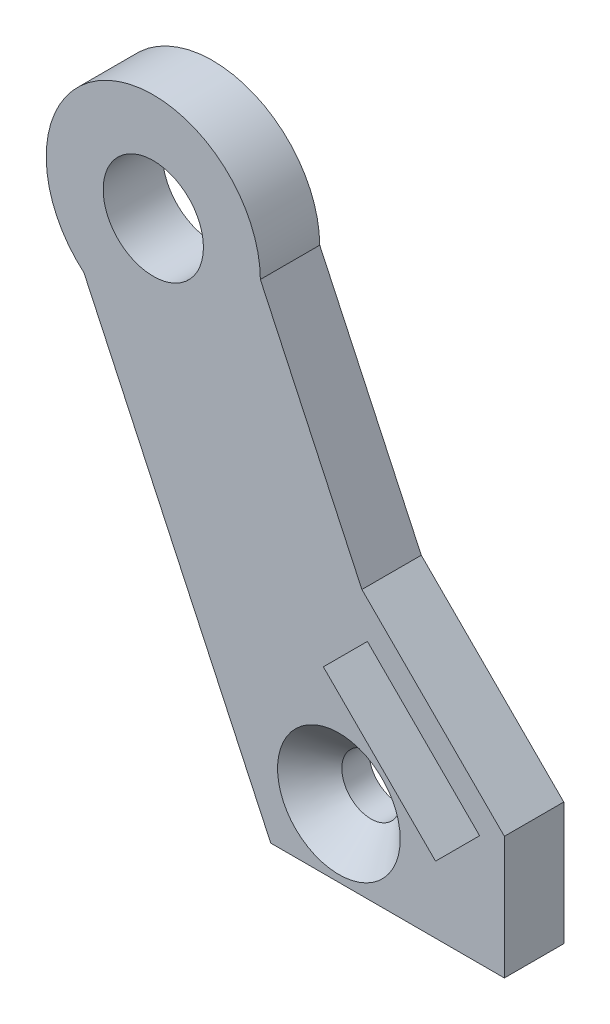
SolidWorks part; units mm, degrees
ref_plane "Front Plane" through (0, 0, 0) normal (0, 0, 1) x (1, 0, 0)
ref_plane "Top Plane" through (0, 0, 0) normal (0, 1, 0) x (1, 0, 0)
ref_plane "Right Plane" through (0, 0, 0) normal (1, 0, 0) x (0, 0, -1)
sketch "Sketch1" plane through (0, 0, 0) normal (0, 0, 1) x (1, 0, 0)
  line L0 (0, 12) -> (12, 0) construction
  line L1 (0, 0) -> (12, 0)
  line L2 (0, 0) -> (0, 12)
  line L3 (0, 12) -> (12, 12)
  line L4 (12, 0) -> (12, 12)
  line L5 (0, 0) -> (3.5, 0)
  line L6 (0, 0) -> (0, 3.5)
  line L7 (0, 3.5) -> (3.5, 3.5)
  line L8 (3.5, 0) -> (3.5, 3.5)
  line L9 (8.2662, 3.6278) -> (8.3192, 3.6808) construction
  line L10 (8.4645, 3.4295) -> (2.7015, 9.1924)
  line L11 (2.7015, 9.1924) -> (4.9643, 11.4551)
  line L12 (8.4645, 3.4295) -> (10.7272, 5.6922)
  line L13 (4.9643, 11.4551) -> (10.7272, 5.6922)
  line L14 (0, 0) -> (-10.5655, 22.6577)
  line L15 (-10.5655, 22.6577) -> (-1.5024, 26.8839)
  line L16 (-1.5024, 26.8839) -> (4.6816, 13.6223)
  line L17 (4.6816, 13.6223) -> (12, 6.3039)
  line L18 (12, 0) -> (8.5175, 3.4825)
  circle A0 centre (3.5, 3.5) radius 1.5
  circle A1 centre (-6.0339, 24.7708) radius 2.575
  circle A3 centre (-6.0339, 24.7708) radius 5.5
  dimension "D5" = 3
  dimension "D6" = 5.15
  dimension "D7" = 11
  dimension "D1" = 12
  dimension "D2" = 12
  dimension "D3" = 3.5
  dimension "D4" = 3.5
  dimension "D8" = 45
  dimension "D9" = 25
  dimension "D10" = 90
  dimension "D11" = 90
  dimension "D12" = 14.6325
  dimension "D13" = 10.3498
  dimension "D14" = 3.2
  dimension "D15" = 8.15
  dimension "D16" = 0.075
  dimension "D17" = 4.925
  dimension "D19" = 160
extrude "Boss-Extrude1" add sketch "Sketch1" along normal blind 3.05 contours L15 A3 A1 | L15 A3 A1 | A3 L14 L2 L10 L11 L13 L3 L17 L16 | L17 L3 L13 L12 L0 L4 | A0 L8 L1 L0 L2 L7 | A0 L7 L2 L1 L8
hole_wizard "CSK for M3 Flat Head Machine Screw1" positions "Sketch2" profile "Sketch3" countersink size "M3" standard "ANSI Metric" end condition through all
sketch "Sketch2" plane through (0, 0, 3.05) normal (0, 0, 1) x (1, 0, 0)
  point P0 (3.5, 3.5)
sketch "Sketch3" plane through (3.5, 3.5, 3.05) normal (1, 0, 0) x (0, -1, 0)
  line L0 (0, 0) -> (0, 3.05)
  line L1 (0, 3.05) -> (1.5, 3.05)
  line L2 (1.5, 3.05) -> (1.5, 1.65)
  line L3 (1.5, 1.65) -> (3.15, 0)
  line L5 (3.15, 0) -> (0, 0)
  line L6 (-1.5, 1.65) -> (-3.15, 0) construction
  line L11 (0, -6.35) -> (0, 107.95) construction
  dimension "Thru Hole Dia." = 3
  dimension "Thru Hole Depth" = 3.05
  dimension "Near C'Sink Dia." = 6.3
  dimension "Near C'Sink Angle" = 90
